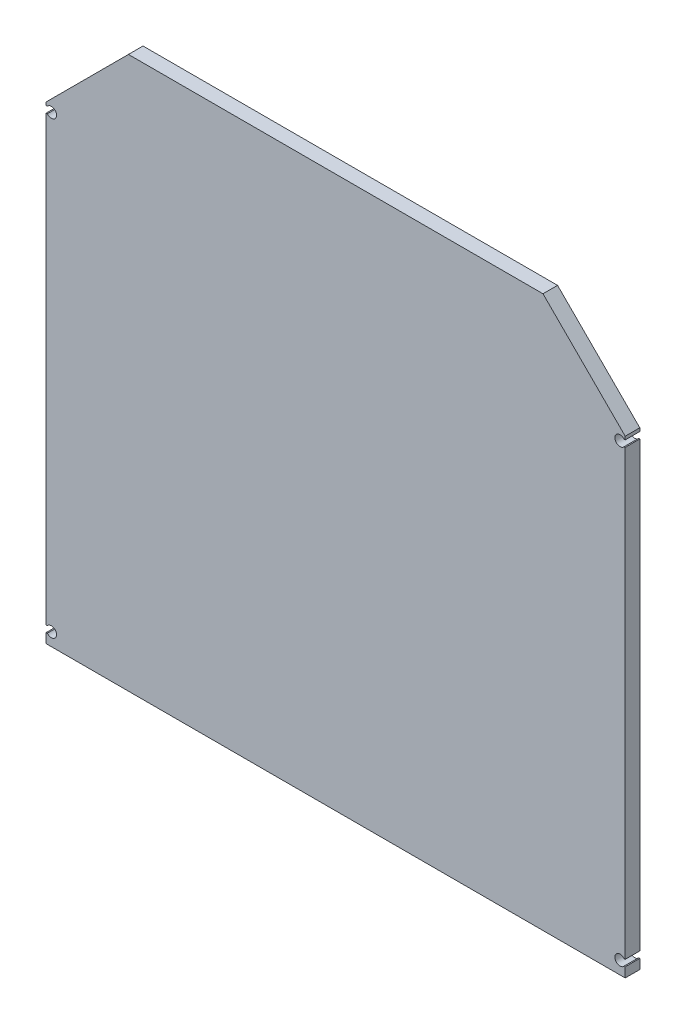
SolidWorks part; units mm, degrees
material "Acrylic (Medium-high impact)"
ref_plane "Front Plane" through (0, 0, 0) normal (0, 0, 1) x (1, 0, 0)
ref_plane "Top Plane" through (0, 0, 0) normal (0, 1, 0) x (1, 0, 0)
ref_plane "Right Plane" through (0, 0, 0) normal (1, 0, 0) x (0, 0, -1)
sketch "Sketch5" plane through (0, 0, 0) normal (0, 0, 1) x (1, 0, 0)
  line L0 (-111.5659, 73.6124) -> (-112.0046, 73.6124)
  line L1 (-111.5659, 71.1124) -> (-112.0046, 71.1124)
  line L2 (-112.0046, 71.1124) -> (-112.0046, -100.425)
  line L3 (-112.0046, -100.425) -> (-111.5659, -100.425)
  line L4 (-111.5659, -102.925) -> (-112.0046, -102.925)
  line L5 (-112.0046, -102.925) -> (-112.0046, -106.675)
  line L6 (-112.0046, -106.675) -> (112.0046, -106.675)
  line L7 (-112.0046, 73.6124) -> (-112.0046, 74.8624)
  line L8 (-112.0046, 74.8624) -> (-80.192, 106.675)
  line L9 (-80.192, 106.675) -> (80.192, 106.675)
  line L10 (80.192, 106.675) -> (112.0046, 74.8624)
  line L11 (112.0046, 74.8624) -> (112.0046, 73.6124)
  line L12 (112.0046, 73.6124) -> (111.5659, 73.6124)
  line L13 (111.5659, 71.1124) -> (112.0046, 71.1124)
  line L14 (112.0046, 71.1124) -> (112.0046, -100.425)
  line L15 (112.0046, -106.675) -> (112.0046, -102.925)
  line L16 (112.0046, -102.925) -> (111.5659, -102.925)
  line L17 (112.0046, -100.425) -> (111.5659, -100.425)
  arc A0 (-111.5659, 71.1124) -> (-111.5659, 73.6124) centre (-110.0046, 72.3624) ccw
  arc A1 (111.5659, 73.6124) -> (111.5659, 71.1124) centre (110.0046, 72.3624) ccw
  arc A2 (111.5659, -100.425) -> (111.5659, -102.925) centre (110.0046, -101.675) ccw
  arc A3 (-111.5659, -100.425) -> (-111.5659, -102.925) centre (-110.0046, -101.675) cw
extrude "Boss-Extrude1" add sketch "Sketch5" along normal blind 5.6388
